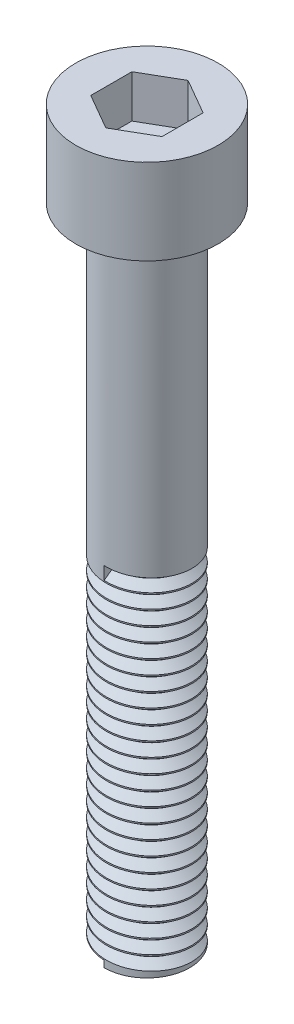
SolidWorks part; units mm, degrees
material "Acero aleado"
ref_plane "Alzado" through (0, 0, 0) normal (0, 0, 1) x (1, 0, 0)
ref_plane "Planta" through (0, 0, 0) normal (0, 1, 0) x (1, 0, 0)
ref_plane "Vista lateral" through (0, 0, 0) normal (1, 0, 0) x (0, 0, -1)
sketch "Sk_Cabeza" plane through (0, 0, 0) normal (0, 1, 0) x (1, 0, 0)
  circle A0 centre (0, 0) radius 5
  dimension "DIAM1" = 10
extrude "Cabeza" add sketch "Sk_Cabeza" along normal blind 6 from offset 0
sketch "Sk_Cana" plane through (0, 0, 0) normal (0, 1, 0) x (1, 0, 0)
  circle A0 centre (0, 0) radius 3
  dimension "DIAM2" = 6
extrude "Cana" add sketch "Sk_Cana" along normal blind 45 from offset 45
ref_plane "Plano_cabeza" through (0, 6, 0) normal (0, 1, 0) x (1, 0, 0)
sketch "Sk_Hueco_Allen" plane through (0, 6, 0) normal (0, 1, 0) x (1, 0, 0)
  line L0 (2.5, -1.4434) -> (0, -2.8868)
  line L1 (0, -2.8868) -> (-2.5, -1.4434)
  line L2 (-2.5, -1.4434) -> (-2.5, 1.4434)
  line L3 (-2.5, 1.4434) -> (0, 2.8868)
  line L4 (0, 2.8868) -> (2.5, 1.4434)
  line L5 (2.5, 1.4434) -> (2.5, -1.4434)
extrude "Hueco_Allen" cut sketch "Sk_Hueco_Allen" against normal blind 3
ref_plane "Plano_punta" through (0, -45, 0) normal (0, 1, 0) x (1, 0, 0)
sketch "Sk_Helice" plane through (0, -45, 0) normal (0, 1, 0) x (1, 0, 0)
  circle A0 centre (0, 0) radius 3
curve "Helice_rosca" pitch 1 height 24 turns 24
sketch "Sk_Perfil_rosca" plane through (0, 0, 0) normal (1, 0, 0) x (0, 0, -1)
  line L0 (-3.2, -45.6) -> (-2.3866, -45)
  line L1 (-2.3866, -45) -> (-3.2, -44.4)
  line L2 (-3.2, -44.4) -> (-3.2, -45.6)
sweep "Rosca_M6x1,0" cut profiles "Sk_Perfil_rosca" path "Helice_rosca"
